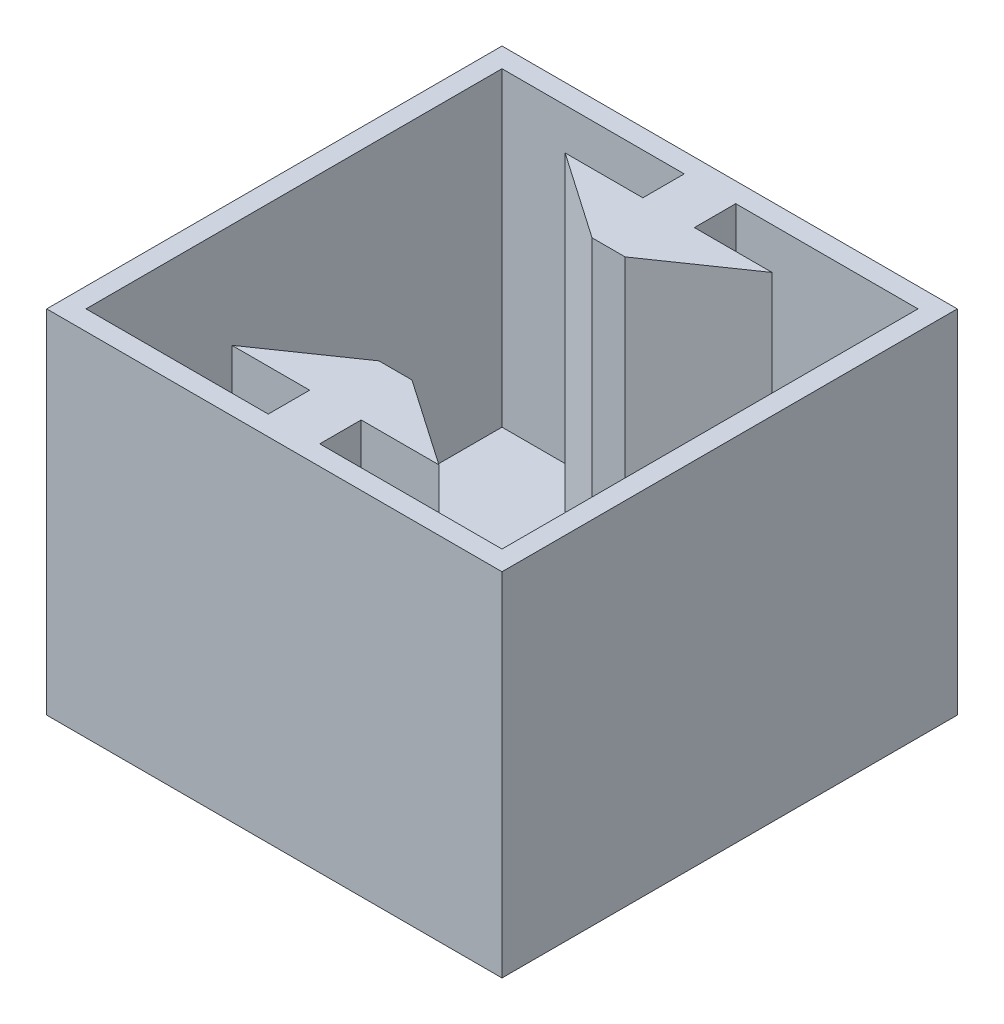
SolidWorks part; units mm, degrees
ref_plane "Front Plane" through (0, 0, 0) normal (0, 0, 1) x (1, 0, 0)
ref_plane "Top Plane" through (0, 0, 0) normal (0, 1, 0) x (1, 0, 0)
ref_plane "Right Plane" through (0, 0, 0) normal (1, 0, 0) x (0, 0, -1)
sketch "Sketch1" plane through (0, 0, 0) normal (0, 1, 0) x (1, 0, 0)
  line L0 (0, 2.4761) -> (0, 12.2727) construction
  line L1 (-10.05, 10.05) -> (10.05, 10.05)
  line L2 (-10.05, 10.05) -> (-10.05, -10.05)
  line L3 (-10.05, -10.05) -> (10.05, -10.05)
  line L4 (10.05, 10.05) -> (10.05, -10.05)
  line L5 (-10.05, 10.05) -> (10.05, -10.05) construction
  line L6 (-10.05, -10.05) -> (10.05, 10.05) construction
  line L7 (-11, 11) -> (11, 11)
  line L8 (-11, 11) -> (-11, -11)
  line L9 (-11, -11) -> (11, -11)
  line L10 (11, 11) -> (11, -11)
  line L11 (-11, 11) -> (11, -11) construction
  line L12 (-11, -11) -> (11, 11) construction
  line L13 (-0.7991, 5.15) -> (0.7991, 5.15)
  line L14 (0.7991, 5.15) -> (5, 8.05)
  line L15 (5, 8.05) -> (1.245, 8.05)
  line L16 (1.245, 8.05) -> (1.245, 10.05)
  line L17 (-1.245, 8.05) -> (-1.245, 10.05)
  line L18 (-5, 8.05) -> (-1.245, 8.05)
  line L19 (-0.7991, 5.15) -> (-5, 8.05)
  line L20 (10.05, 0) -> (-10.05, 0) construction
  line L21 (-1.245, -8.05) -> (-1.245, -10.05)
  line L22 (-5, -8.05) -> (-1.245, -8.05)
  line L23 (-0.7991, -5.15) -> (-5, -8.05)
  line L24 (-0.7991, -5.15) -> (0.7991, -5.15)
  line L25 (0.7991, -5.15) -> (5, -8.05)
  line L26 (5, -8.05) -> (1.245, -8.05)
  line L27 (1.245, -8.05) -> (1.245, -10.05)
  point P0 (0, 0)
  point P6 (0, 0)
  point P22 (0, 5.15)
  dimension "D1" = 20.1
  dimension "D2" = 22
  dimension "D3" = 2
  dimension "D4" = 2.49
  dimension "D5" = 4.9
  dimension "D6" = 5
extrude "Boss-Extrude1" add sketch "Sketch1" along normal blind 15 contours L10 L7 L8 L9 L1 L4 L3 L2 | L19 L13 L14 L15 L16 L1 L17 L18 | L27 L26 L25 L24 L23 L22 L21 L3
sketch "Sketch2" plane through (0, 0, 0) normal (0, -1, 0) x (1, 0, 0)
  line L2 (-11, 11) -> (11, 11)
  line L3 (-11, 11) -> (-11, -11)
  line L4 (-11, -11) -> (11, -11)
  line L5 (11, 11) -> (11, -11)
  line L6 (-11, 11) -> (11, -11) construction
  line L7 (-11, -11) -> (11, 11) construction
  point P2 (0, 0)
extrude "Boss-Extrude2" add sketch "Sketch2" along normal blind 2
